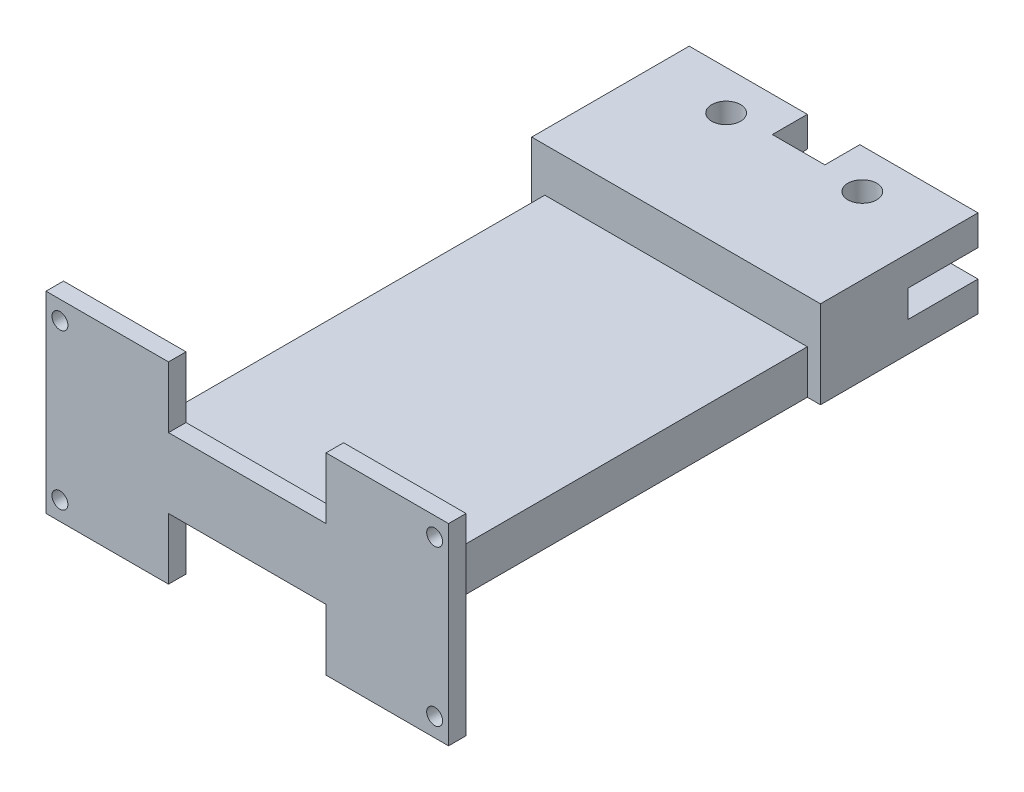
SolidWorks part; units mm, degrees
ref_plane "前视基准面" through (0, 0, 0) normal (0, 0, 1) x (1, 0, 0)
ref_plane "上视基准面" through (0, 0, 0) normal (0, 1, 0) x (1, 0, 0)
ref_plane "右视基准面" through (0, 0, 0) normal (1, 0, 0) x (0, 0, -1)
sketch "草图1" plane through (0, 0, 0) normal (1, 0, 0) x (0, 0, -1)
  line L1 (9, -5) -> (-9, -5)
  line L2 (9, -5) -> (9, 5)
  line L3 (9, 5) -> (-9, 5)
  line L4 (-9, -5) -> (-9, 5)
  line L5 (9, -5) -> (-9, 5) construction
  line L6 (9, 5) -> (-9, -5) construction
  point P0 (0, 0)
  dimension "D1" = 18
  dimension "D2" = 10
extrude "凸台-拉伸1" add sketch "草图1" against normal mid plane 33
sketch "草图2" plane through (-16.5, 0, 0) normal (-1, 0, 0) x (0, 0, 1)
  line L0 (-1, -1.55) -> (-9, -1.55)
  line L1 (-1, -1.55) -> (-1, 1.55)
  line L2 (-9, -1.55) -> (-9, 1.55)
  line L3 (-1, 1.55) -> (-9, 1.55)
  line L4 (-1, -1.55) -> (-9, 1.55) construction
  line L5 (-9, -1.55) -> (-1, 1.55) construction
  line L6 (-9, -5) -> (-9, 5) construction
  point P1 (-5, 0)
  dimension "D1" = 3.1
  dimension "D2" = 8
extrude "切除-拉伸1" cut sketch "草图2" against normal blind 40
sketch "草图3" plane through (0, 5, 0) normal (0, 1, 0) x (1, 0, 0)
  line L0 (0, -5.5) -> (0, 5.5) construction
  circle A0 centre (-7.78, 4.5) radius 1.65
  circle A1 centre (7.78, 4.5) radius 1.65
  dimension "D1" = 15.56
  dimension "D2" = 4.5
  dimension "D3" = 3.3
extrude "切除-拉伸2" cut sketch "草图3" against normal blind 20
sketch "草图5" plane through (0, 5, 0) normal (0, 1, 0) x (1, 0, 0)
  line L0 (-16.5, 9) -> (16.5, 9) construction
  line L1 (-3, 13) -> (3, 13)
  line L2 (-3, 13) -> (-3, 5)
  line L3 (-3, 5) -> (3, 5)
  line L4 (3, 13) -> (3, 5)
  line L5 (-3, 13) -> (3, 5) construction
  line L6 (-3, 5) -> (3, 13) construction
  point P0 (0, 9)
  dimension "D1" = 8
  dimension "D2" = 6
extrude "切除-拉伸3" cut sketch "草图5" against normal blind 20
sketch "草图6" plane through (0, 0, 9) normal (0, 0, 1) x (1, 0, 0)
  line L0 (-16.5, -5) -> (16.5, -5) construction
  line L1 (-15, -5) -> (15, -5)
  line L2 (-15, -5) -> (-15, 0)
  line L3 (-15, 0) -> (15, 0)
  line L4 (15, -5) -> (15, 0)
  line L5 (-15, -5) -> (15, 0) construction
  line L6 (-15, 0) -> (15, -5) construction
  point P0 (0, -2.5)
  point P5 (0, 0)
  dimension "D1" = 30
  dimension "D2" = 5
extrude "凸台-拉伸2" add sketch "草图6" along normal blind 47
sketch "草图7" plane through (0, 0, 56) normal (0, 0, 1) x (1, 0, 0)
  line L0 (0, -5.5) -> (0, 5.5) construction
  line L1 (-23, -11) -> (23, -11)
  line L2 (-23, -11) -> (-23, 11)
  line L3 (-23, 11) -> (23, 11)
  line L4 (23, -11) -> (23, 11)
  line L5 (-23, -11) -> (23, 11) construction
  line L6 (-23, 11) -> (23, -11) construction
  line L7 (18.15, 0) -> (-18.15, 0) construction
  circle A0 centre (-21.41, 8.87) radius 0.91
  circle A1 centre (21.41, 8.87) radius 0.91
  circle A2 centre (21.41, -8.87) radius 0.91
  circle A3 centre (-21.41, -8.87) radius 0.91
  point P0 (0, 0)
  dimension "D2" = 17.74
  dimension "D3" = 42.82
  dimension "D5" = 1.82
  dimension "D1" = 46
  dimension "D4" = 22
extrude "凸台-拉伸3" add sketch "草图7" along normal blind 2
sketch "草图8" plane through (0, 0, 58) normal (0, 0, 1) x (1, 0, 0)
  line L0 (-9, 4) -> (-9, 11)
  line L1 (-9, 4) -> (9, 4)
  line L2 (-9, 11) -> (9, 11)
  line L3 (9, 4) -> (9, 11)
  line L4 (-9, 4) -> (9, 11) construction
  line L5 (-9, 11) -> (9, 4) construction
  line L6 (23, 11) -> (-23, 11) construction
  line L7 (18.15, 0) -> (-18.15, 0) construction
  line L8 (-9, -11) -> (9, -4) construction
  line L9 (-9, -4) -> (9, -11) construction
  line L10 (9, -4) -> (9, -11)
  line L11 (-9, -11) -> (9, -11)
  line L12 (-9, -4) -> (9, -4)
  line L13 (-9, -4) -> (-9, -11)
  point P1 (0, 7.5)
  point P14 (0, -7.5)
  dimension "D1" = 7
  dimension "D2" = 18
extrude "切除-拉伸4" cut sketch "草图8" against normal blind 10
